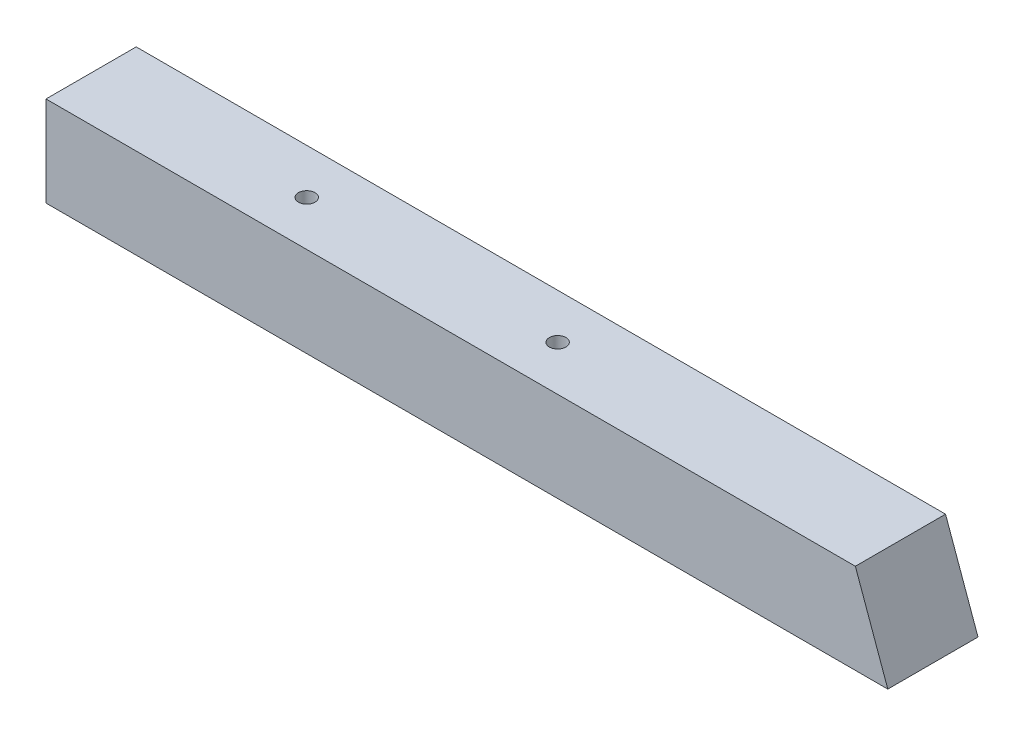
SolidWorks part; units mm, degrees
material "Pine"
ref_plane "X-Y Datum" through (0, 0, 0) normal (0, 0, 1) x (1, 0, 0)
ref_plane "X-Z Datum" through (0, 0, 0) normal (0, 1, 0) x (1, 0, 0)
ref_plane "Y-Z Datum" through (0, 0, 0) normal (1, 0, 0) x (0, 0, -1)
sketch "Sketch1" plane through (0, 0, 0) normal (1, 0, 0) x (0, 0, -1)
  line L1 (-19.05, 19.05) -> (19.05, 19.05)
  line L2 (-19.05, 19.05) -> (-19.05, -19.05)
  line L3 (-19.05, -19.05) -> (19.05, -19.05)
  line L4 (19.05, 19.05) -> (19.05, -19.05)
  line L5 (-19.05, 19.05) -> (19.05, -19.05) construction
  line L6 (-19.05, -19.05) -> (19.05, 19.05) construction
  point P0 (0, 0)
  dimension "D1" = 38.1
extrude "Boss-Extrude1" add sketch "Sketch1" along normal blind 355.6
sketch "Sketch2" plane through (0, 0, 19.05) normal (0, 0, 1) x (1, 0, 0)
  line L0 (355.6, -19.05) -> (341.8907, 19.05)
  line L1 (355.6, 19.05) -> (0, 19.05) construction
  line L5 (355.6, 19.05) -> (355.6, -19.05) construction
  line L6 (341.8907, 19.05) -> (355.6, 19.05)
  line L7 (355.6, 19.05) -> (355.6, -19.05)
  dimension "D1" = 19.79
extrude "Cut-Extrude1" cut sketch "Sketch2" against normal through all
sketch "Sketch3" plane through (0, -19.05, 0) normal (0, -1, 0) x (-1, 0, 0)
  line L0 (-91.0884, 0) -> (-197.0874, 0) construction
  line L1 (0, -19.05) -> (0, 19.05) construction
  circle A0 centre (-91.0884, 0) radius 3.5
  circle A1 centre (-197.0874, 0) radius 3.5
  dimension "D2" = 7
  dimension "D1" = 105.999
  dimension "D3" = 91.0884
extrude "Cut-Extrude2" cut sketch "Sketch3" against normal through all both
